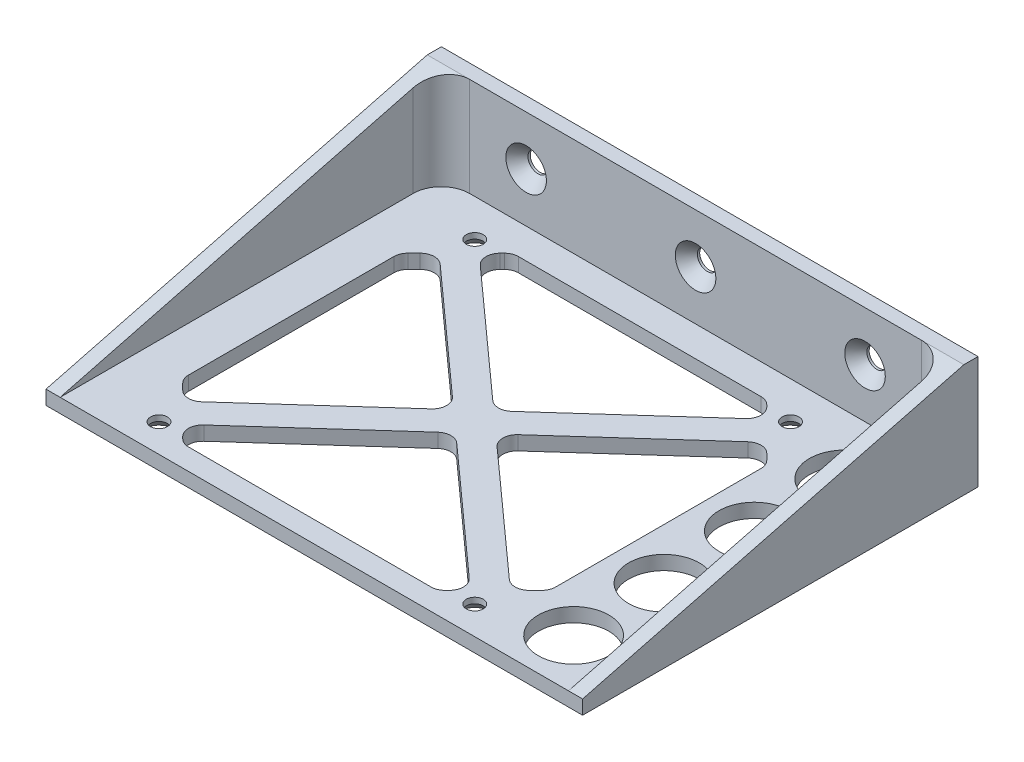
SolidWorks part; units mm, degrees
material "6061-T6 (SS)"
ref_plane "Front Plane" through (0, 0, 0) normal (0, 0, 1) x (1, 0, 0)
ref_plane "Top Plane" through (0, 0, 0) normal (0, 1, 0) x (1, 0, 0)
ref_plane "Right Plane" through (0, 0, 0) normal (1, 0, 0) x (0, 0, -1)
sketch "Sketch1" plane through (0, 0, 0) normal (0, 1, 0) x (1, 0, 0)
  line L1 (-60.325, -44.45) -> (60.325, -44.45)
  line L2 (-60.325, -44.45) -> (-60.325, 44.45)
  line L3 (-60.325, 44.45) -> (60.325, 44.45)
  line L4 (60.325, -44.45) -> (60.325, 44.45)
  line L5 (-60.325, -44.45) -> (60.325, 44.45) construction
  line L6 (-60.325, 44.45) -> (60.325, -44.45) construction
  point P0 (0, 0)
  dimension "D1" = 88.9
  dimension "D2" = 120.65
extrude "Boss-Extrude1" add sketch "Sketch1" along normal blind 3.175
sketch "Sketch2" plane through (0, 3.175, 0) normal (0, 1, 0) x (1, 0, 0)
  line L0 (60.325, -44.45) -> (60.325, 44.45) construction
  line L1 (-60.325, 44.45) -> (60.325, 44.45)
  line L2 (-60.325, 44.45) -> (-60.325, 41.275)
  line L3 (-60.325, 41.275) -> (60.325, 41.275)
  line L4 (60.325, 44.45) -> (60.325, 41.275)
  dimension "D1" = 3.175
extrude "Boss-Extrude2" add sketch "Sketch2" along normal blind 22.225
hole_wizard "CSK for #6 Flat Head Machine Screw1" positions "Sketch5" profile "Sketch4" countersink size "#6" standard "Ansi Inch" end condition up to next
sketch "Sketch5" plane through (0, 0, 0) normal (0, -1, 0) x (1, 0, 0)
  line L0 (-60.325, 44.45) -> (60.325, 44.45) construction
  line L1 (-60.325, -44.45) -> (-60.325, 44.45) construction
  point P0 (29.725, 38.1)
  point P1 (29.725, -32.9)
  point P4 (-41.275, -32.9)
  point P6 (-41.275, 38.1)
  dimension "D1" = 19.05
  dimension "D2" = 71
  dimension "D3" = 71
  dimension "D4" = 6.35
sketch "Sketch4" plane through (29.725, 0, 38.1) normal (1, 0, 0) x (0, 0, -1)
  line L0 (0, 0) -> (0, 3.175)
  line L1 (0, 3.175) -> (1.8986, 3.175)
  line L2 (1.8986, 3.175) -> (1.8986, 1.892)
  line L3 (1.8986, 1.892) -> (3.5433, 0)
  line L5 (3.5433, 0) -> (0, 0)
  line L6 (-1.8986, 1.892) -> (-3.5433, 0) construction
  line L11 (0, -6.35) -> (0, 107.95) construction
  dimension "Thru Hole Dia." = 3.7973
  dimension "Thru Hole Depth" = 3.175
  dimension "Near C'Sink Dia." = 7.0866
  dimension "Near C'Sink Angle" = 82
sketch "Sketch6" plane through (0, 0, 0) normal (0, -1, 0) x (1, 0, 0)
  line L0 (-41.275, 38.1) -> (29.725, -32.9) construction
  line L1 (-47.05, 26.984) -> (-42.6086, 31.4254)
  line L2 (-34.35, -34.484) -> (22.8, -34.484)
  line L3 (-47.05, -21.784) -> (-47.05, 26.984)
  line L4 (-34.35, 39.684) -> (22.8, 39.684)
  line L5 (35.5, -21.784) -> (35.5, 26.984)
  line L6 (-47.05, -34.484) -> (35.5, 39.684) construction
  line L7 (-47.05, 39.684) -> (35.5, -34.484) construction
  line L8 (22.8, 39.684) -> (26.5621, 35.9219)
  line L9 (-47.05, -21.784) -> (-42.6086, -26.2254)
  line L10 (22.8, -34.484) -> (26.5621, -30.7219)
  line L11 (-42.6086, 31.4254) -> (-10.5256, 2.6)
  line L12 (-38.1121, -30.7219) -> (-5.775, -1.6683)
  line L13 (-38.1121, 35.9219) -> (-5.775, 6.8683)
  line L14 (-42.6086, -26.2254) -> (-10.5256, 2.6)
  line L15 (-44.928, 42.0458) -> (37.622, -32.1222) construction
  line L16 (-49.172, 37.3222) -> (33.378, -36.8458) construction
  line L17 (-38.1121, 35.9219) -> (-34.35, 39.684)
  line L18 (-49.172, -32.1222) -> (33.378, 42.0458) construction
  line L19 (31.0586, 31.4254) -> (35.5, 26.984)
  line L20 (-44.928, -36.8458) -> (37.622, 37.3222) construction
  line L21 (-1.0244, 2.6) -> (31.0586, 31.4254)
  line L22 (-1.0244, 2.6) -> (31.0586, -26.2254)
  line L23 (-5.775, 6.8683) -> (26.5621, 35.9219)
  line L24 (-8.0233, 4.8483) -> (-8.1503, 4.7341)
  line L25 (-5.775, -1.6683) -> (26.5621, -30.7219)
  line L26 (-3.3997, 0.4659) -> (-3.5267, 0.3517)
  line L27 (31.0586, -26.2254) -> (35.5, -21.784)
  line L28 (-38.1121, -30.7219) -> (-34.35, -34.484)
  point P4 (-5.775, 2.6)
  dimension "D1" = 82.55
  dimension "D2" = 74.168
  dimension "D3" = 3.175
  dimension "D4" = 3.175
extrude "Cut-Extrude1" cut sketch "Sketch6" against normal through all contours L9 L14 L11 L1 L3 | L13 L23 L8 L4 L17 | L22 L27 L5 L19 L21 | L12 L28 L2 L10 L25
fillet "Fillet2" radius 3.175 20 edges at (26.5621, 1.5875, 35.9219) (-38.1121, 1.5875, 35.9219) (-5.775, 1.5875, 6.8683) (-5.775, 1.5875, -1.6683) (-1.0244, 1.5875, 2.6) (31.0586, 1.5875, 31.4254) (31.0586, 1.5875, -26.2254) (26.5621, 1.5875, -30.7219) (-38.1121, 1.5875, -30.7219) (-42.6086, 1.5875, -26.2254) (-10.5256, 1.5875, 2.6) (-42.6086, 1.5875, 31.4254) (-34.35, 1.5875, 39.684) (22.8, 1.5875, 39.684) (35.5, 1.5875, 26.984) (35.5, 1.5875, -21.784) (22.8, 1.5875, -34.484) (-34.35, 1.5875, -34.484) (-47.05, 1.5875, -21.784) (-47.05, 1.5875, 26.984)
sketch "Sketch9" plane through (-60.325, 0, 0) normal (-1, 0, 0) x (0, 0, 1)
  line L0 (-41.275, 25.4) -> (44.45, 3.175)
  line L1 (-41.275, 25.4) -> (-41.275, 3.175) construction
  line L2 (-41.275, 3.175) -> (44.45, 3.175) construction
  line L3 (-41.275, 25.4) -> (-41.275, 3.175)
  line L4 (-41.275, 3.175) -> (44.45, 3.175)
extrude "Boss-Extrude3" add sketch "Sketch9" against normal blind 3.175
fillet "Fillet3" radius 6.35 1 edges at (-57.15, 14.2875, -41.275)
mirror "Mirror1" about plane through (0, 0, 0) normal (1, 0, 0) of "Boss-Extrude3", "Fillet3"
hole_wizard "CSK for #8 Flat Head Socket Cap Screw1" positions "Sketch11" profile "Sketch10" countersink size "#8" standard "Ansi Inch" end condition through all
sketch "Sketch11" plane through (0, 0, -41.275) normal (0, 0, 1) x (1, 0, 0)
  line L0 (-50.8, 14.2875) -> (50.8, 14.2875) construction
  line L1 (-50.8, 25.4) -> (-50.8, 3.175) construction
  line L2 (50.8, 3.175) -> (50.8, 25.4) construction
  point P0 (-38.1, 14.2875)
  point P1 (38.1, 14.2875)
  point P3 (0, 14.2875)
  dimension "D1" = 38.1
  dimension "D2" = 38.1
sketch "Sketch10" plane through (-38.1, 14.2875, -41.275) normal (1, 0, 0) x (0, -1, 0)
  line L0 (0, 0) -> (0, 3.175)
  line L1 (0, 3.175) -> (2.2479, 3.175)
  line L2 (2.2479, 3.175) -> (2.2479, 2.659)
  line L3 (2.2479, 2.659) -> (4.5593, 0)
  line L5 (4.5593, 0) -> (0, 0)
  line L6 (-2.2479, 2.659) -> (-4.5593, 0) construction
  line L11 (0, -6.35) -> (0, 107.95) construction
  dimension "Thru Hole Dia." = 4.4958
  dimension "Thru Hole Depth" = 3.175
  dimension "Near C'Sink Dia." = 9.1186
  dimension "Near C'Sink Angle" = 82
sketch "Sketch12" plane through (0, 3.175, 0) normal (0, 1, 0) x (1, 0, 0)
  line L5 (46.93, 7.56) -> (46.93, -12.76) construction
  line L6 (3.7263, -2.6) -> (60.325, -2.6) construction
  line L7 (60.325, -44.45) -> (60.325, 41.275) construction
  line L8 (35.5, 20.4689) -> (35.5, -25.6689) construction
  circle A0 centre (46.93, 27.88) radius 7.9375
  circle A1 centre (46.93, 7.56) radius 7.9375
  circle A2 centre (46.93, -12.76) radius 7.9375
  circle A3 centre (46.93, -33.08) radius 7.9375
  point P12 (46.93, -2.6)
  dimension "D5" = 15.875
  dimension "D1" = 20.32
  dimension "D2" = 20.32
  dimension "D3" = 20.32
  dimension "D4" = 11.43
extrude "Cut-Extrude2" cut sketch "Sketch12" against normal up to next
